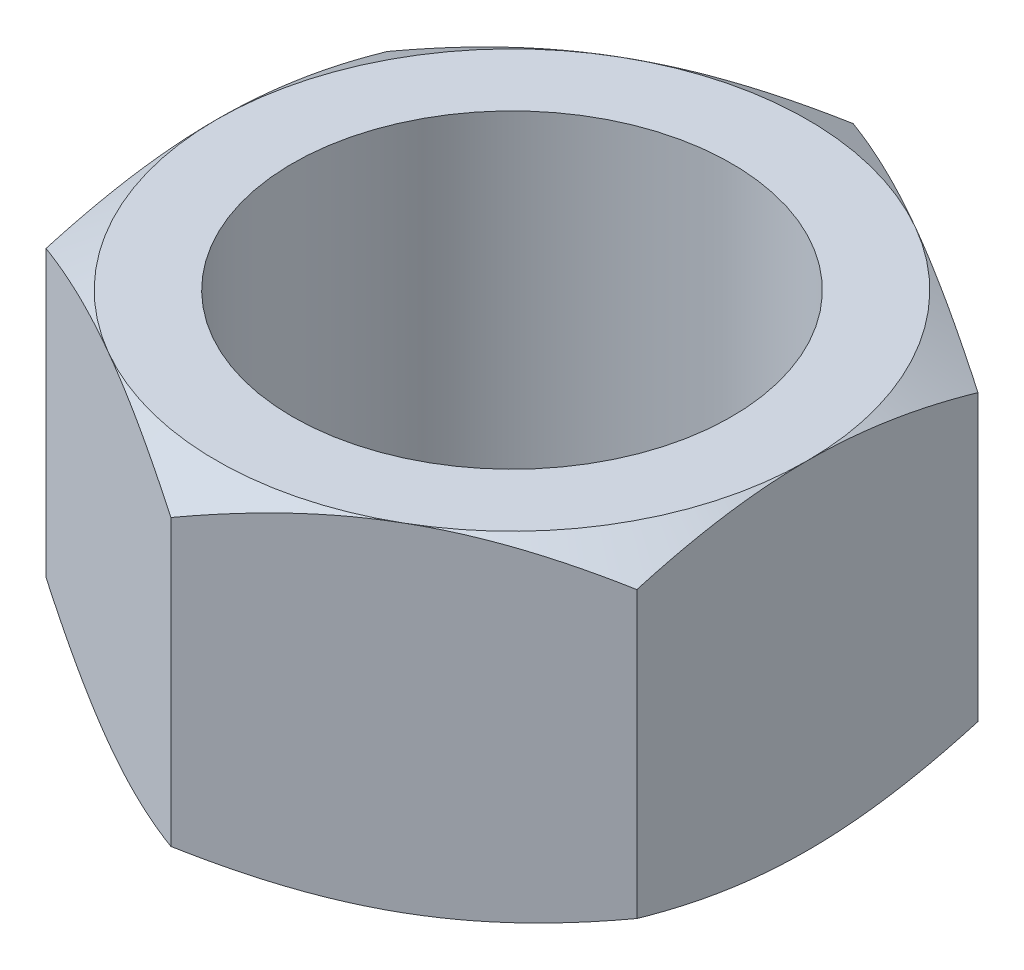
SolidWorks part; units mm, degrees
ref_plane "Front Plane" through (0, 0, 0) normal (0, 0, 1) x (1, 0, 0)
ref_plane "Top Plane" through (0, 0, 0) normal (0, 1, 0) x (1, 0, 0)
ref_plane "Right Plane" through (0, 0, 0) normal (1, 0, 0) x (0, 0, -1)
sketch "Sketch1" plane through (0, 0, 0) normal (0, 1, 0) x (1, 0, 0)
  line L1 (0, 5.1326) -> (-4.445, 2.5663)
  line L2 (-4.445, 2.5663) -> (-4.445, -2.5663)
  line L3 (-4.445, -2.5663) -> (0, -5.1326)
  line L4 (0, -5.1326) -> (4.445, -2.5663)
  line L5 (4.445, -2.5663) -> (4.445, 2.5663)
  line L6 (4.445, 2.5663) -> (0, 5.1326)
  circle A0 centre (0, 0) radius 4.445 construction
  circle A1 centre (0, 0) radius 3.302
  dimension "D2" = 6.604
  dimension "D1" = 8.89
extrude "Boss-Extrude1" add sketch "Sketch1" along normal mid plane 5.08
sketch "Sketch2" plane through (0, 2.54, 0) normal (0, 1, 0) x (1, 0, 0)
  line L0 (0, 5.1326) -> (-4.445, 2.5663) construction
  circle A0 centre (0, 0) radius 4.445
extrude "Cut-Extrude1" cut sketch "Sketch2" against normal blind 5.08 draft 60 flip side to cut
sketch "Sketch3" plane through (0, -2.54, 0) normal (0, -1, 0) x (-1, 0, 0)
  circle A0 centre (0, 0) radius 4.445
extrude "Cut-Extrude2" cut sketch "Sketch3" against normal blind 5.08 draft 60 flip side to cut
